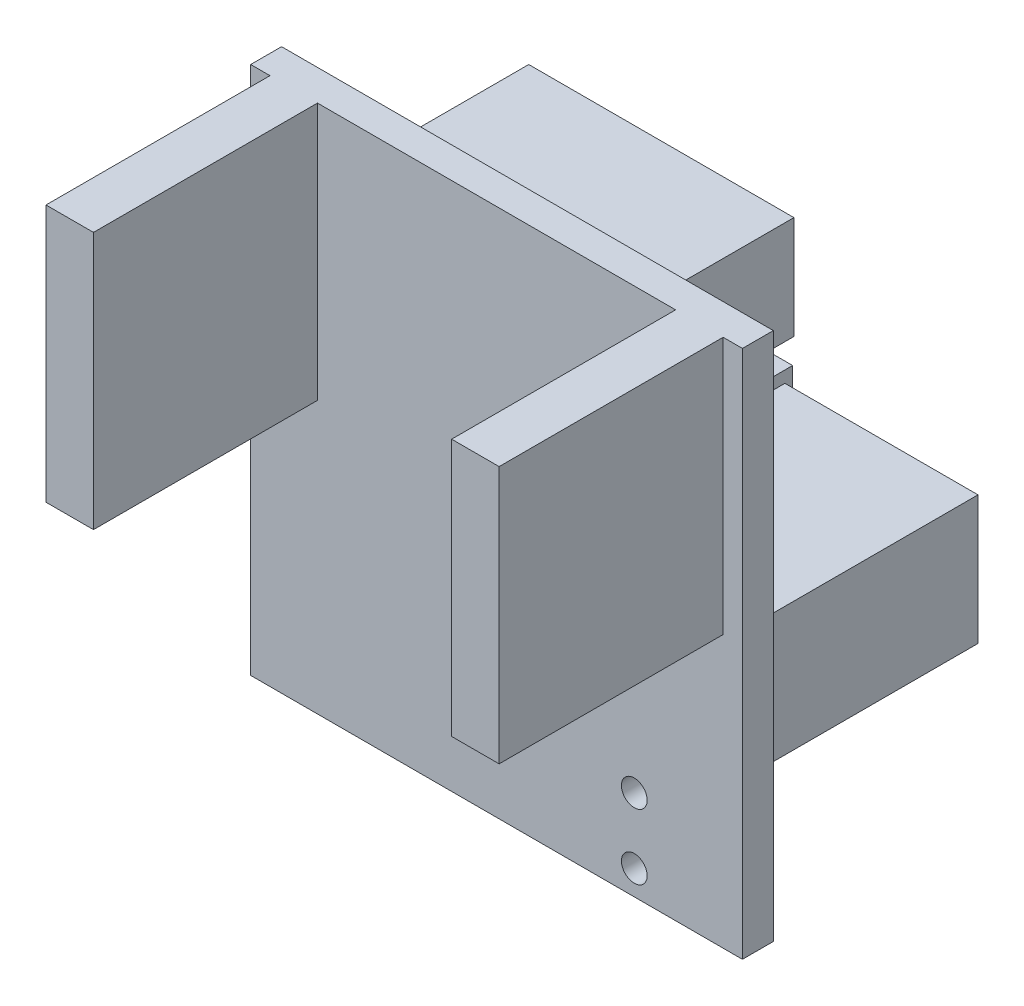
SolidWorks part; units mm, degrees
ref_plane "正面" through (0, 0, 0) normal (0, 0, 1) x (1, 0, 0)
ref_plane "平面" through (0, 0, 0) normal (0, 1, 0) x (1, 0, 0)
ref_plane "右側面" through (0, 0, 0) normal (1, 0, 0) x (0, 0, -1)
sketch "ｽｹｯﾁ1" plane through (0, 0, 0) normal (0, 0, 1) x (1, 0, 0)
  line L1 (-9.55, 10.275) -> (9.55, 10.275)
  line L2 (-9.55, 10.275) -> (-9.55, -10.275)
  line L3 (-9.55, -10.275) -> (9.55, -10.275)
  line L4 (9.55, 10.275) -> (9.55, -10.275)
  line L5 (-9.55, 10.275) -> (9.55, -10.275) construction
  line L6 (-9.55, -10.275) -> (9.55, 10.275) construction
  point P0 (0, 0)
  dimension "D1" = 20.55
  dimension "D2" = 19.1
extrude "ﾎﾞｽ - 押し出し1" add sketch "ｽｹｯﾁ1" along normal blind 1.2
sketch "ｽｹｯﾁ2" plane through (0, 0, 1.2) normal (0, 0, 1) x (1, 0, 0)
  line L0 (9.55, 10.275) -> (-9.55, 10.275) construction
  line L1 (8.8, 10.275) -> (6.9556, 10.275)
  line L2 (8.8, 10.275) -> (8.8, 0.275)
  line L3 (8.8, 0.275) -> (6.9556, 0.275)
  line L4 (6.9556, 10.275) -> (6.9556, 0.275)
  line L5 (9.55, -10.275) -> (9.55, 10.275) construction
  dimension "D1" = 10
  dimension "D2" = 0.75
extrude "ﾎﾞｽ - 押し出し2" add sketch "ｽｹｯﾁ2" along normal blind 8.7
mirror "ﾐﾗｰ1" about plane through (0, 0, 0) normal (1, 0, 0) of "ﾎﾞｽ - 押し出し2"
sketch "ｽｹｯﾁ3" plane through (0, 0, 0) normal (0, 0, -1) x (-1, 0, 0)
  line L0 (9.55, -10.275) -> (-9.55, -10.275) construction
  line L1 (-1.3, 0.025) -> (-8.8, 0.025)
  line L2 (-1.3, 0.025) -> (-1.3, -4.975)
  line L3 (-1.3, -4.975) -> (-8.8, -4.975)
  line L4 (-8.8, 0.025) -> (-8.8, -4.975)
  line L5 (-9.55, -10.275) -> (-9.55, 10.275) construction
  dimension "D1" = 5.3
  dimension "D2" = 0.75
  dimension "D3" = 7.5
  dimension "D4" = 5
extrude "ﾎﾞｽ - 押し出し3" add sketch "ｽｹｯﾁ3" along normal blind 8.7
sketch "ｽｹｯﾁ4" plane through (0, 0, 0) normal (0, 0, -1) x (-1, 0, 0)
  line L0 (9.55, -10.275) -> (-9.55, -10.275) construction
  line L1 (8.7, -1.525) -> (0.7, -1.525)
  line L2 (8.7, -1.525) -> (8.7, -9.075)
  line L3 (8.7, -9.075) -> (0.7, -9.075)
  line L4 (0.7, -1.525) -> (0.7, -9.075)
  line L5 (9.55, 10.275) -> (9.55, -10.275) construction
  dimension "D1" = 1.2
  dimension "D2" = 7.55
  dimension "D3" = 8
  dimension "D4" = 0.85
extrude "ﾎﾞｽ - 押し出し4" add sketch "ｽｹｯﾁ4" along normal blind 11
sketch "ｽｹｯﾁ5" plane through (0, 0, 0) normal (0, 0, -1) x (-1, 0, 0)
  line L0 (-9.55, 10.275) -> (9.55, 10.275) construction
  line L1 (4.45, 9.975) -> (-5.85, 9.975)
  line L2 (4.45, 9.975) -> (4.45, 5.975)
  line L3 (4.45, 5.975) -> (-5.85, 5.975)
  line L4 (-5.85, 9.975) -> (-5.85, 5.975)
  line L5 (-9.55, -10.275) -> (-9.55, 10.275) construction
  dimension "D1" = 0.3
  dimension "D2" = 3.7
  dimension "D3" = 10.3
  dimension "D4" = 4
extrude "ﾎﾞｽ - 押し出し5" add sketch "ｽｹｯﾁ5" along normal blind 4.5
sketch "ｽｹｯﾁ6" plane through (0, 0, 0) normal (0, 0, -1) x (-1, 0, 0)
  line L0 (-9.55, -10.275) -> (-9.55, 10.275) construction
  line L1 (9.55, -10.275) -> (-9.55, -10.275) construction
  circle A0 centre (-5.35, -6.775) radius 0.5
  circle A1 centre (-5.35, -9.315) radius 0.5
  point P6 (0, 0)
  point P8 (-11.7245, -8.5773)
  point P10 (0, 0)
  dimension "D4" = 1
  dimension "D1" = 4.2
  dimension "D2" = 3.5
  dimension "D3" = 2.54
extrude "ｶｯﾄ - 押し出し1" cut sketch "ｽｹｯﾁ6" against normal through all
